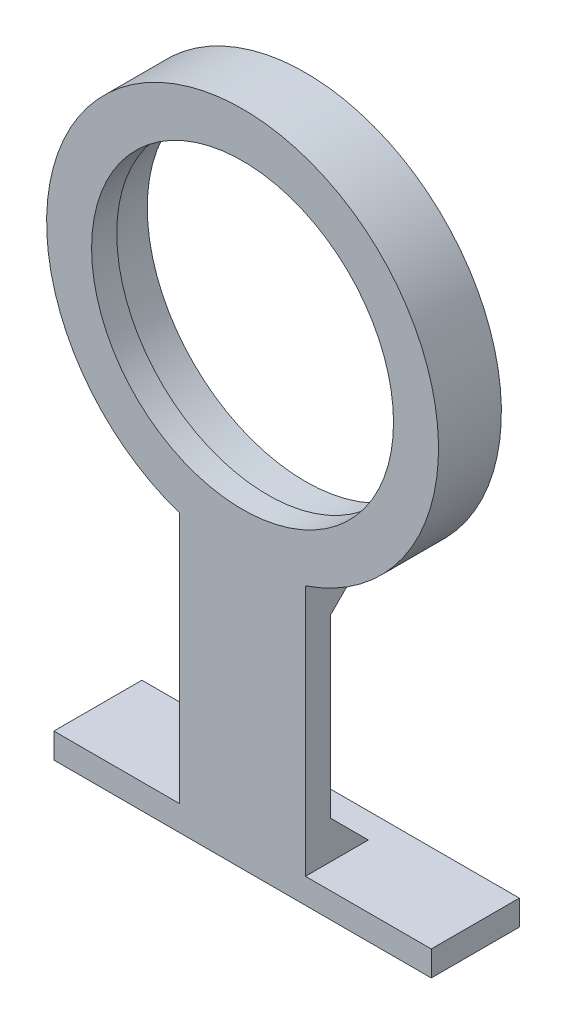
SolidWorks part; units mm, degrees
ref_plane "Front Plane" through (0, 0, 0) normal (0, 0, 1) x (1, 0, 0)
ref_plane "Top Plane" through (0, 0, 0) normal (0, 1, 0) x (1, 0, 0)
ref_plane "Right Plane" through (0, 0, 0) normal (1, 0, 0) x (0, 0, -1)
sketch "Sketch1" plane through (0, 0, 0) normal (0, 0, 1) x (1, 0, 0)
  line L0 (5, -34.7506) -> (15, -34.7506)
  line L1 (-5, -14.7506) -> (5, -14.7506) construction
  line L2 (-5, -14.7506) -> (-5, -34.7506)
  line L4 (5, -14.7506) -> (5, -34.7506)
  line L5 (-15, -34.7506) -> (-5, -34.7506)
  line L6 (-15, -34.7506) -> (-15, -36.7506)
  line L7 (-15, -36.7506) -> (15, -36.7506)
  line L8 (15, -34.7506) -> (15, -36.7506)
  circle A0 centre (0, 0) radius 12.575
  arc A1 (5, -14.7506) -> (-5, -14.7506) centre (0, 0) ccw
  point P8 (0, -14.7506)
  point P13 (0, -36.7506)
  point P14 (-5, -14.6714)
  dimension "D1" = 25.15
  dimension "D2" = 3
  dimension "D3" = 30
  dimension "D4" = 2
  dimension "D5" = 20
  dimension "D6" = 10
extrude "Boss-Extrude1" add sketch "Sketch1" along normal blind 2 and the other way blind 1 contours A1 L2 L5 L6 L7 L8 L0 L4
sketch "Sketch2" plane through (0, 0, 2) normal (0, 0, 1) x (1, 0, 0)
  line L7 (-5, -14.7506) -> (-5, -34.7506)
  line L8 (-5, -34.7506) -> (-15, -34.7506)
  line L9 (-15, -34.7506) -> (-15, -36.7506)
  line L10 (-15, -36.7506) -> (15, -36.7506)
  line L11 (15, -36.7506) -> (15, -34.7506)
  line L12 (15, -34.7506) -> (5, -34.7506)
  line L13 (5, -34.7506) -> (5, -14.7506)
  line L14 (-5, -14.7506) -> (-5, -34.7506)
  line L15 (-5, -34.7506) -> (-15, -34.7506)
  line L16 (-15, -34.7506) -> (-15, -36.7506)
  line L17 (-15, -36.7506) -> (15, -36.7506)
  line L18 (15, -36.7506) -> (15, -34.7506)
  line L19 (15, -34.7506) -> (5, -34.7506)
  line L20 (5, -34.7506) -> (5, -14.7506)
  circle A0 centre (0, 0) radius 12
  arc A1 (5, -14.7506) -> (-5, -14.7506) centre (0, 0) ccw
  arc A2 (5, -14.7506) -> (-5, -14.7506) centre (0, 0) ccw
  dimension "D2" = 24
  dimension "D1" = 0
extrude "Boss-Extrude2" add sketch "Sketch2" along normal blind 2
sketch "Sketch3" plane through (0, 0, 4) normal (0, 0, 1) x (1, 0, 0)
  line L1 (-15, -34.7506) -> (15, -34.7506)
  line L2 (-15, -34.7506) -> (-15, -36.7506)
  line L3 (-15, -36.7506) -> (15, -36.7506)
  line L4 (15, -34.7506) -> (15, -36.7506)
sketch "Sketch4" plane through (-5, 0, 0) normal (-1, 0, 0) x (0, 0, 1)
  line L0 (-1, -14.7506) -> (2, -17.7506)
  line L1 (2, -17.7506) -> (2, -31.7506)
  line L2 (2, -31.7506) -> (-1, -34.7506)
  line L3 (-1, -14.7506) -> (-1, -34.7506) construction
  line L4 (-1, -14.7506) -> (-1, -34.7506)
  dimension "D1" = 45
  dimension "D2" = 45
  dimension "D3" = 3
extrude "Cut-Extrude1" cut sketch "Sketch4" against normal through all
sketch "Sketch5" plane through (0, 0, -1) normal (0, 0, -1) x (-1, 0, 0)
  line L6 (15, -34.7506) -> (5, -34.7506)
  line L7 (5, -34.7506) -> (-5, -34.7506)
  line L8 (-5, -34.7506) -> (-15, -34.7506)
  line L9 (-15, -34.7506) -> (-15, -36.7506)
  line L10 (-15, -36.7506) -> (15, -36.7506)
  line L11 (15, -36.7506) -> (15, -34.7506)
  line L12 (15, -34.7506) -> (5, -34.7506)
  line L13 (5, -34.7506) -> (-5, -34.7506)
  line L14 (-5, -34.7506) -> (-15, -34.7506)
  line L15 (-15, -34.7506) -> (-15, -36.7506)
  line L16 (-15, -36.7506) -> (15, -36.7506)
  line L17 (15, -36.7506) -> (15, -34.7506)
  dimension "D1" = 0
extrude "Boss-Extrude3" add sketch "Sketch5" along normal blind 2
